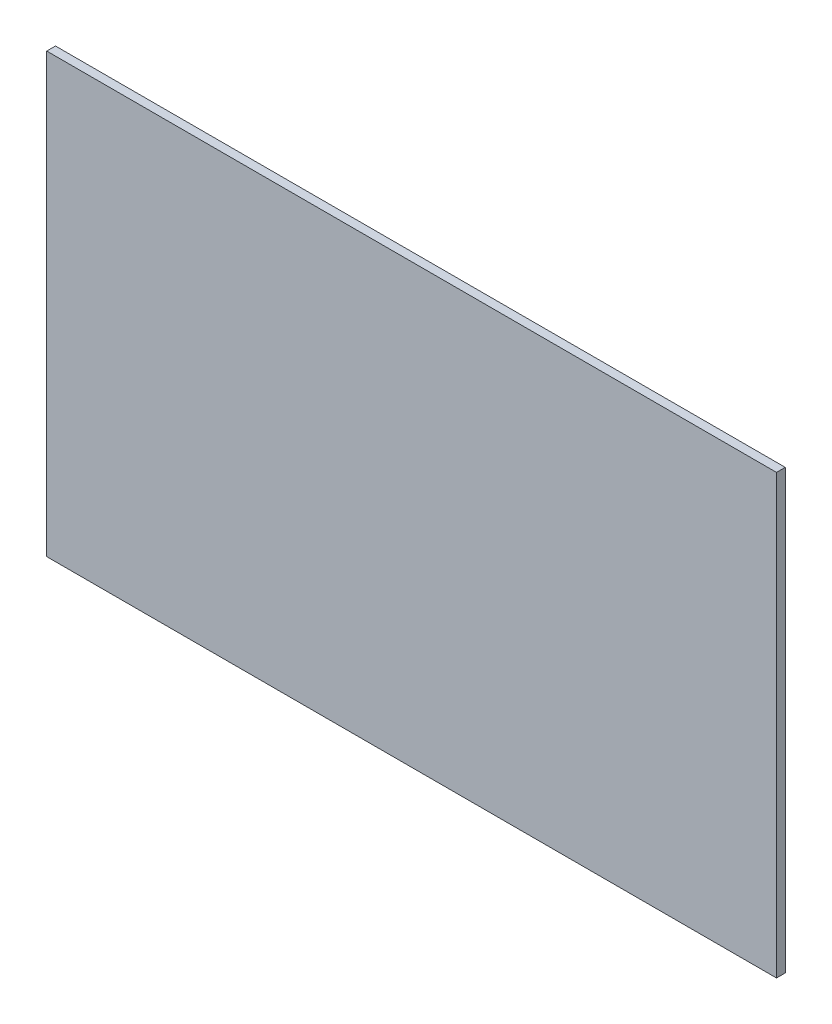
SolidWorks part; units mm, degrees
ref_plane "Front Plane" through (0, 0, 0) normal (0, 0, 1) x (1, 0, 0)
ref_plane "Top Plane" through (0, 0, 0) normal (0, 1, 0) x (1, 0, 0)
ref_plane "Right Plane" through (0, 0, 0) normal (1, 0, 0) x (0, 0, -1)
sketch "Sketch1" plane through (0, 0, 0) normal (0, 0, 1) x (1, 0, 0)
  line L1 (0, 0) -> (250, 0)
  line L2 (0, 0) -> (0, 150)
  line L3 (0, 150) -> (250, 150)
  line L4 (250, 0) -> (250, 150)
  dimension "D1" = 250
  dimension "D2" = 150
extrude "Boss-Extrude1" add sketch "Sketch1" along normal blind 3
